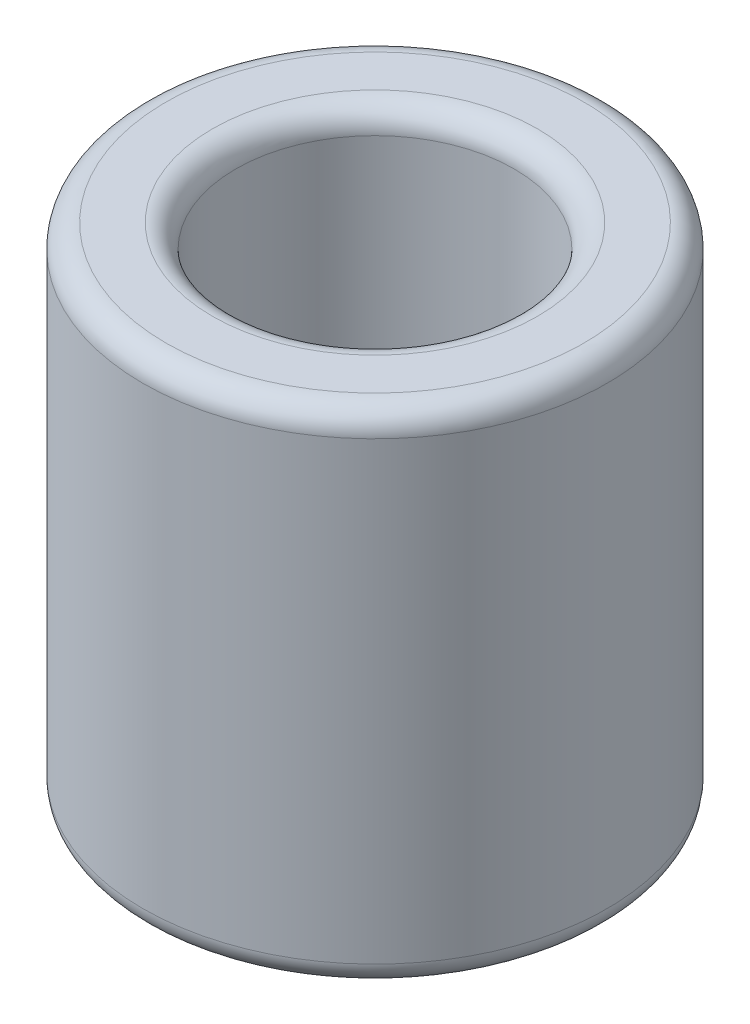
SolidWorks part; units mm, degrees
ref_plane "Front" through (0, 0, 0) normal (0, 0, 1) x (1, 0, 0)
ref_plane "Top" through (0, 0, 0) normal (0, 1, 0) x (1, 0, 0)
ref_plane "Right" through (0, 0, 0) normal (1, 0, 0) x (0, 0, -1)
sketch "Sketch1" plane through (0, 0, 0) normal (0, 1, 0) x (1, 0, 0)
  circle A0 centre (0, 0) radius 2.5
  circle A1 centre (0, 0) radius 1.5
  dimension "D1" = 5
  dimension "D2" = 3
extrude "Boss-Extrude1" add sketch "Sketch1" along normal blind 5.4
fillet "Fillet1" radius 0.25 4 edges at (0, 0, 1.5) (0, 5.4, 1.5) (0, 0, 2.5) (0, 5.4, 2.5)
